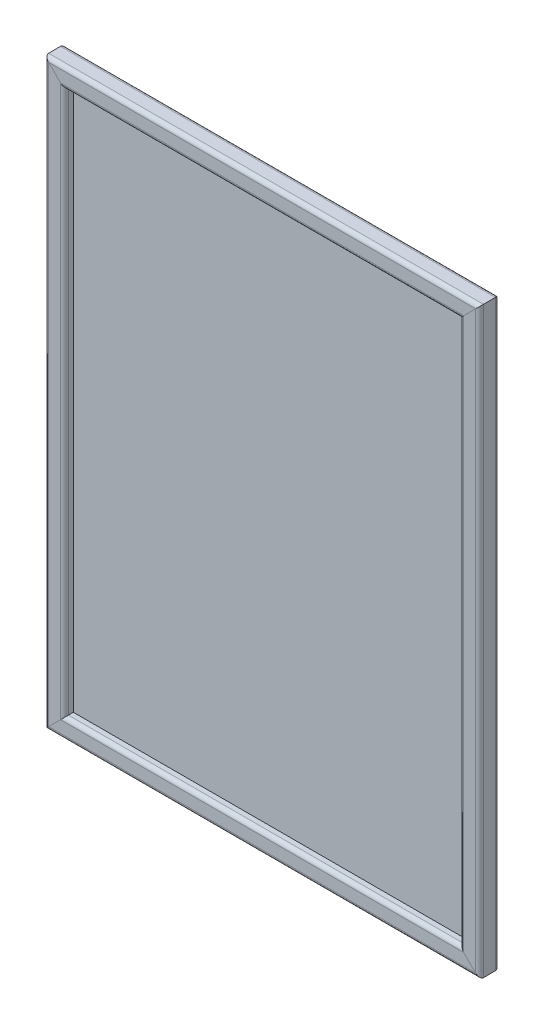
SolidWorks part; units mm, degrees
ref_plane "Płaszczyzna przednia" through (0, 0, 0) normal (0, 0, 1) x (1, 0, 0)
ref_plane "Płaszczyzna górna" through (0, 0, 0) normal (0, 1, 0) x (1, 0, 0)
ref_plane "Płaszczyzna prawa" through (0, 0, 0) normal (1, 0, 0) x (0, 0, -1)
sketch3d "Szkic 3D1"
  line L1 (0, 0, 0) -> (420, 0, 0)
  line L2 (0, 0, 0) -> (0, 570, 0)
  line L3 (0, 570, 0) -> (420, 570, 0)
  line L4 (420, 0, 0) -> (420, 570, 0)
  point P5 (0, 0, 0)
  dimension "D1" = 570
  dimension "D2" = 420
sketch "Szkic9" plane through (0, 0, 0) normal (0, 0, 1) x (1, 0, 0)
  line L0 (0, 0) -> (0, 570) construction
  line L1 (10, 10) -> (410, 10)
  line L2 (10, 10) -> (10, 560)
  line L3 (10, 560) -> (410, 560)
  line L4 (410, 10) -> (410, 560)
  line L5 (0, 0) -> (420, 0) construction
  dimension "D1" = 550
  dimension "D2" = 400
  dimension "D3" = 10
  dimension "D4" = 10
other "Rura kwadratowa 20 X 20 X 2(1)"
ref_plane "Płaszczyzna3" through (0, 0, 0) normal (0, 1, 0) x (1, 0, 0)
sketch "Sketch1" plane through (0, 0, 0) normal (0, 1, 0) x (1, 0, 0)
  line L0 (-6, -8) -> (6, -8)
  line L1 (-8, -6) -> (-8, 6)
  line L2 (6, 8) -> (-6, 8)
  line L3 (8, 6) -> (8, -6)
  line L4 (-6, -10) -> (6, -10)
  line L5 (-10, -6) -> (-10, 6)
  line L6 (6, 10) -> (-6, 10)
  line L7 (10, 6) -> (10, -6)
  arc A0 (10, 6) -> (6, 10) centre (6, 6) ccw
  arc A1 (6, -10) -> (10, -6) centre (6, -6) ccw
  arc A2 (-10, -6) -> (-6, -10) centre (-6, -6) ccw
  arc A3 (-6, 10) -> (-10, 6) centre (-6, 6) ccw
  arc A4 (-6, 8) -> (-8, 6) centre (-6, 6) ccw
  arc A5 (8, 6) -> (6, 8) centre (6, 6) ccw
  arc A6 (6, -8) -> (8, -6) centre (6, -6) ccw
  arc A7 (-8, -6) -> (-6, -8) centre (-6, -6) ccw
  point P0 (-10, 0)
  point P1 (10, 0)
  point P2 (0, 10)
  point P3 (0, -10)
  point P4 (0, 0)
  point P5 (-10, -10)
  point P6 (10, -10)
  point P7 (10, 10)
  point P8 (-10, 10)
  point P33 (0, 0)
  dimension "D1" = 4
  dimension "Thickness" = 2
  dimension "V_leg" = 20
extrude "Dodanie-wyciągnięcie1" add sketch "Szkic9" against normal blind 1 and the other way blind 1 separate body
